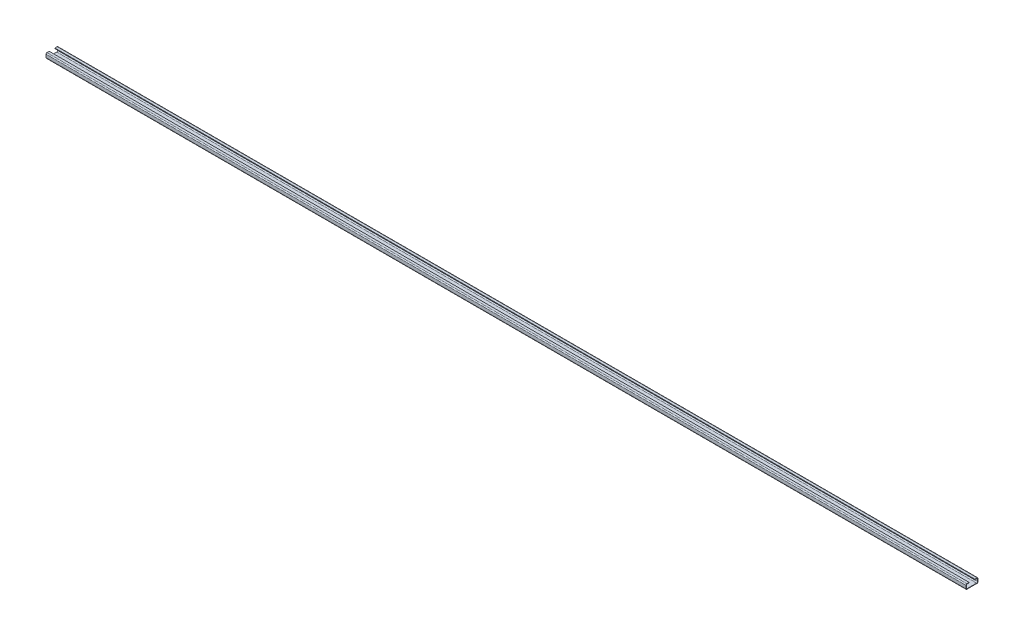
SolidWorks part; units mm, degrees
material "AISI 1045 Aço, trefilado"
ref_plane "Plano frontal" through (0, 0, 0) normal (0, 0, 1) x (1, 0, 0)
ref_plane "Plano superior" through (0, 0, 0) normal (0, 1, 0) x (1, 0, 0)
ref_plane "Plano direito" through (0, 0, 0) normal (1, 0, 0) x (0, 0, -1)
sketch "Esboço1" plane through (0, 0, 0) normal (1, 0, 0) x (0, 0, -1)
  line L0 (-34.75, 12.25) -> (-34.75, -12.25)
  line L1 (-37.5, 15) -> (-17.5, 15)
  line L2 (-37.5, 15) -> (-37.5, -15)
  line L3 (-37.5, -15) -> (37.5, -15)
  line L4 (37.5, 15) -> (37.5, -15)
  line L5 (-37.5, 15) -> (37.5, -15) construction
  line L6 (-37.5, -15) -> (37.5, 15) construction
  line L7 (-34.75, -12.25) -> (34.75, -12.25)
  line L8 (34.75, 12.25) -> (34.75, -12.25)
  line L9 (-34.75, 12.25) -> (-17.5, 12.25)
  line L10 (-17.5, 15) -> (-17.5, 12.25)
  line L13 (17.5, 15) -> (17.5, 12.25)
  line L14 (17.5, 12.25) -> (34.75, 12.25)
  line L15 (-34.75, 12.25) -> (34.75, 12.25) construction
  line L16 (17.5, 15) -> (37.5, 15)
  line L17 (-37.5, 15) -> (37.5, 15) construction
  point P0 (0, 0)
  dimension "D1" = 75
  dimension "D2" = 30
  dimension "D4" = 20
  dimension "D5" = 20
  dimension "D3" = 2.75
extrude "Ressalto-extrusão1" add sketch "Esboço1" along normal blind 5700
fillet "Filete1" radius 6 8 edges at (2850, 12.25, -34.75) (2850, 12.25, 34.75) (2850, 15, 37.5) (2850, 15, -37.5) (2850, -15, -37.5) (2850, -12.25, -34.75) (2850, -12.25, 34.75) (2850, -15, 37.5)
